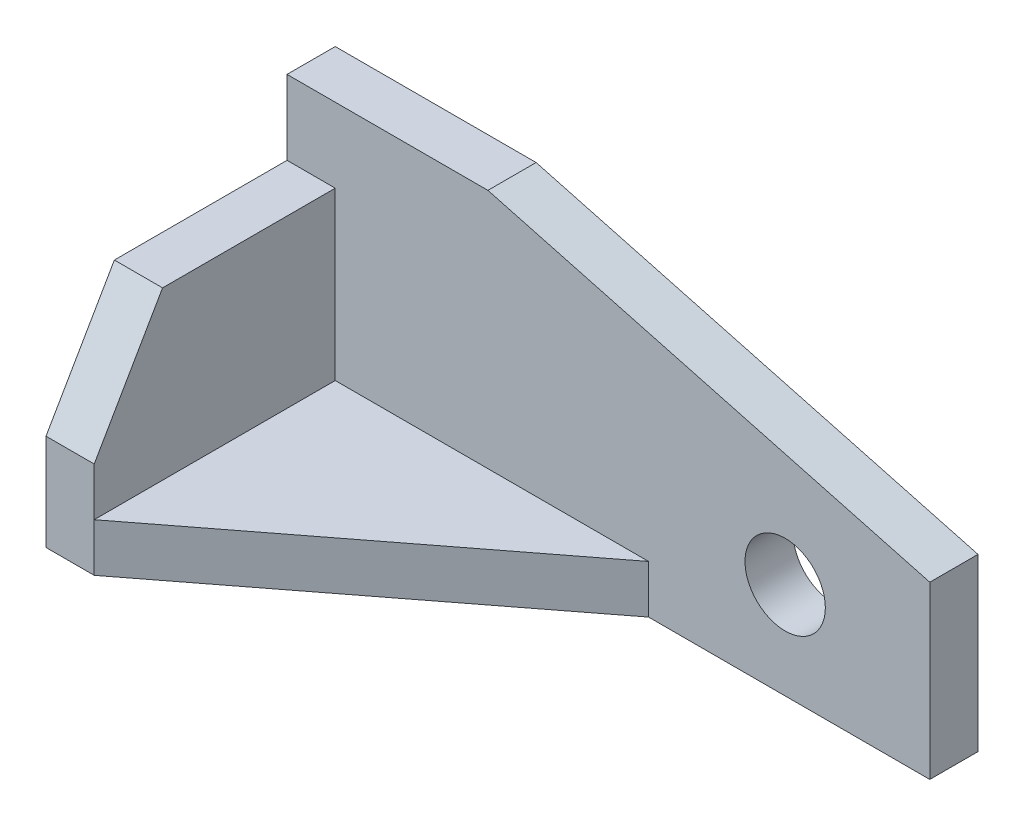
SolidWorks part; units mm, degrees
ref_plane "前基準面" through (0, 0, 0) normal (0, 0, 1) x (1, 0, 0)
ref_plane "上基準面" through (0, 0, 0) normal (0, 1, 0) x (1, 0, 0)
ref_plane "右基準面" through (0, 0, 0) normal (1, 0, 0) x (0, 0, -1)
sketch "草圖1" plane through (0, 0, 0) normal (0, 0, 1) x (1, 0, 0)
  line L0 (0, 0) -> (80, 0)
  line L1 (80, 0) -> (80, 21.2628)
  line L2 (80, 21.2628) -> (25, 36)
  line L3 (25, 36) -> (0, 36)
  line L4 (0, 36) -> (0, 0)
  circle A0 centre (62, 12) radius 5
  point P10 (79.0025, 0)
  point P11 (75.7044, 4.9472)
  dimension "D7" = 10
  dimension "D1" = 18
  dimension "D2" = 12
  dimension "D3" = 25
  dimension "D4" = 80
  dimension "D5" = 15
  dimension "D6" = 36
extrude "填料-伸長1" add sketch "草圖1" against normal blind 6
sketch "草圖2" plane through (0, 0, 0) normal (1, 0, 0) x (0, 0, -1)
  line L0 (0, 0) -> (-30, 0)
  line L1 (-30, 0) -> (-30, 12)
  line L2 (-30, 12) -> (-21.4928, 26.7348)
  line L3 (-21.4928, 26.7348) -> (0, 26.7348)
  line L4 (0, 21.2628) -> (0, 36) construction
  line L5 (0, 26.7348) -> (0, 0)
  dimension "D1" = 30
  dimension "D2" = 12
  dimension "D3" = 30
  dimension "D4" = 21.4928
extrude "填料-伸長2" add sketch "草圖2" along normal blind 6
sketch "草圖3" plane through (0, 0, 0) normal (0, 1, 0) x (1, 0, 0)
  line L0 (0, 0) -> (45, 0)
  line L1 (80, 0) -> (25, 0) construction
  line L2 (45, 0) -> (6, -30)
  line L3 (6, -30) -> (0, -30)
  line L4 (0, -30) -> (0, 0)
  dimension "D1" = 45
extrude "填料-伸長3" add sketch "草圖3" along normal blind 6
